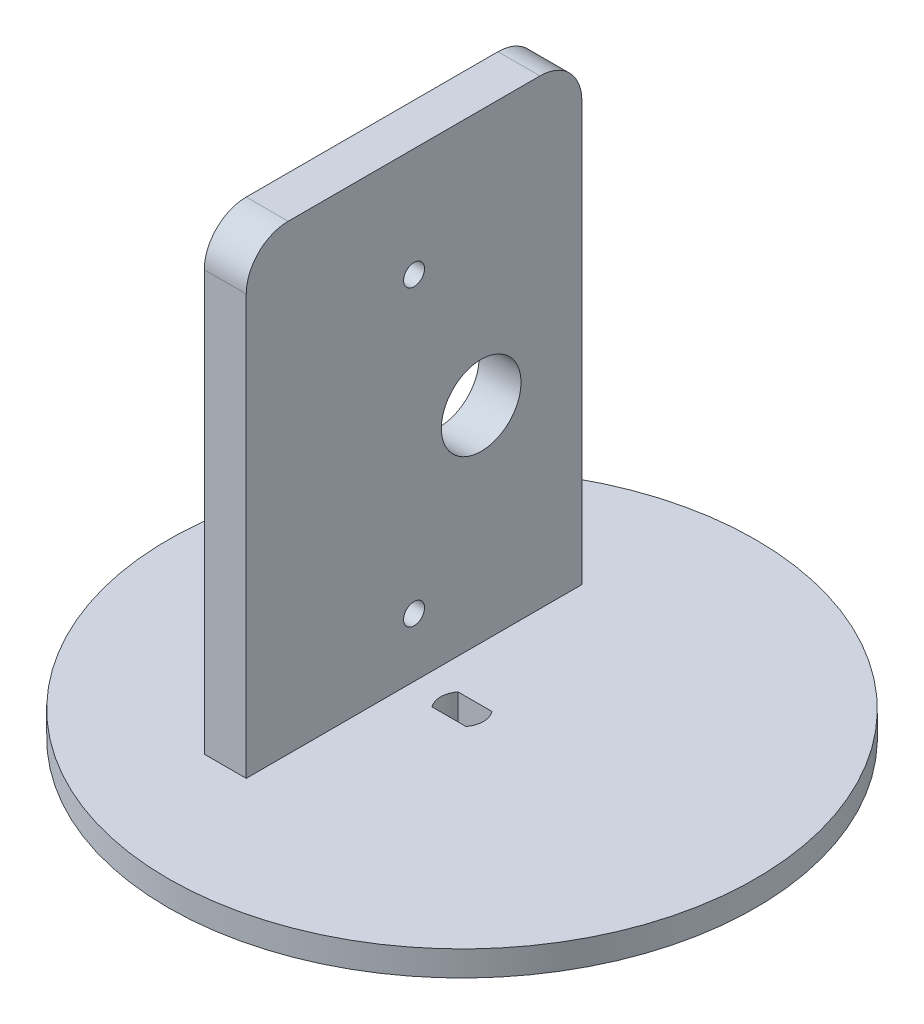
SolidWorks part; units mm, degrees
ref_plane "Alzado" through (0, 0, 0) normal (0, 0, 1) x (1, 0, 0)
ref_plane "Planta" through (0, 0, 0) normal (0, 1, 0) x (1, 0, 0)
ref_plane "Vista lateral" through (0, 0, 0) normal (1, 0, 0) x (0, 0, -1)
sketch "Croquis1" plane through (0, 0, 0) normal (0, 1, 0) x (1, 0, 0)
  line L0 (0, 0) -> (-4.7471, 0) construction
  line L1 (-2.0248, 1.55) -> (2.0248, 1.55)
  line L3 (-2.0248, -1.55) -> (2.0248, -1.55)
  circle A0 centre (0, 0) radius 35
  arc A1 (-2.0248, 1.55) -> (-2.0248, -1.55) centre (0, 0) ccw
  arc A2 (2.0248, -1.55) -> (2.0248, 1.55) centre (0, 0) ccw
  dimension "D1" = 70
  dimension "D2" = 5.1
extrude "Saliente-Extruir1" add sketch "Croquis1" along normal blind 3
sketch "Croquis2" plane through (0, 0, 0) normal (0, -1, 0) x (1, 0, 0)
  line L0 (-2.0248, 1.55) -> (2.0248, 1.55)
  line L1 (-2.0248, -1.55) -> (2.0248, -1.55)
  arc A0 (-2.0248, 1.55) -> (-2.0248, -1.55) centre (0, 0) ccw
  circle A1 centre (0, 0) radius 7.5
  arc A2 (2.0248, -1.55) -> (2.0248, 1.55) centre (0, 0) ccw
  dimension "D2" = 15
extrude "Saliente-Extruir2" add sketch "Croquis2" along normal blind 6
sketch "Croquis3" plane through (0, 0, 1.55) normal (0, 0, -1) x (-1, 0, 0)
  line L0 (-2.0248, -6) -> (2.0248, -6) construction
  circle A0 centre (0, -3) radius 1.25
  dimension "D2" = 2.5
  dimension "D1" = 3
extrude "Cortar-Extruir1" cut sketch "Croquis3" against normal blind 6
sketch "Croquis4" plane through (0, 3, 0) normal (0, 1, 0) x (1, 0, 0)
  line L1 (-5.715, 20) -> (-10.715, 20)
  line L2 (-5.715, 20) -> (-5.715, -20)
  line L3 (-5.715, -20) -> (-10.715, -20)
  line L4 (-10.715, 20) -> (-10.715, -20)
  point P4 (-5.715, 0)
  dimension "D1" = 5
  dimension "D2" = 40
extrude "Saliente-Extruir3" add sketch "Croquis4" along normal blind 55
sketch "Croquis5" plane through (-10.715, 0, 0) normal (-1, 0, 0) x (0, 0, 1)
  line L0 (-20, 3) -> (20, 3) construction
  circle A0 centre (0, 45) radius 1.25
  circle A1 centre (0, 10) radius 1.25
  circle A2 centre (-8, 27.5) radius 4.75
  point P6 (-0.4509, 30.9952)
  point P10 (-5.4179, 30.2891)
  dimension "D1" = 2.5
  dimension "D2" = 2.5
  dimension "D5" = 9.5
  dimension "D3" = 35
  dimension "D4" = 7
  dimension "D6" = 17.5
  dimension "D7" = 8
extrude "Cortar-Extruir2" cut sketch "Croquis5" against normal up to surface (5 mm away) up to face at (-5.715, 30.5, 0)
fillet "Redondeo1" radius 5 2 edges at (-8.215, 58, -20) (-8.215, 58, 20)
